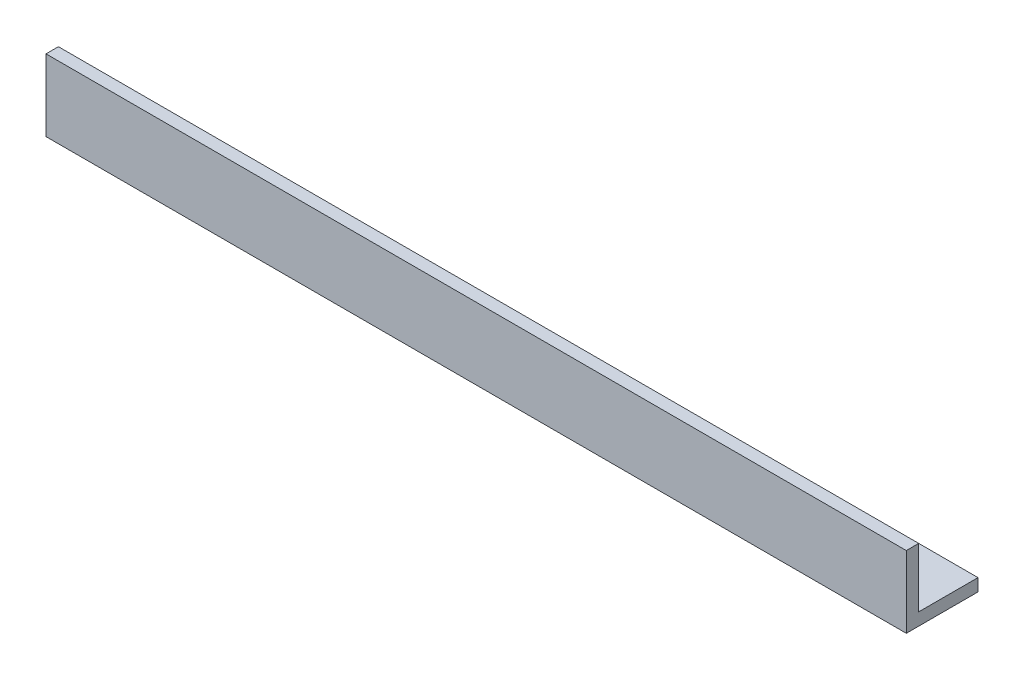
SolidWorks part; units mm, degrees
ref_plane "Front Plane" through (0, 0, 0) normal (0, 0, 1) x (1, 0, 0)
ref_plane "Top Plane" through (0, 0, 0) normal (0, 1, 0) x (1, 0, 0)
ref_plane "Right Plane" through (0, 0, 0) normal (1, 0, 0) x (0, 0, -1)
sketch "Sketch1" plane through (0, 0, 0) normal (1, 0, 0) x (0, 0, -1)
  line L0 (0, 0) -> (20, 0)
  line L1 (20, 0) -> (20, 3.4612)
  line L2 (20, 3.4612) -> (3.4612, 3.4612)
  line L3 (3.4612, 3.4612) -> (3.4612, 20)
  line L4 (3.4612, 20) -> (0, 20)
  line L5 (0, 20) -> (0, 0)
  dimension "D1" = 3.4612
  dimension "D2" = 20
extrude "Boss-Extrude1" add sketch "Sketch1" along normal blind 240
